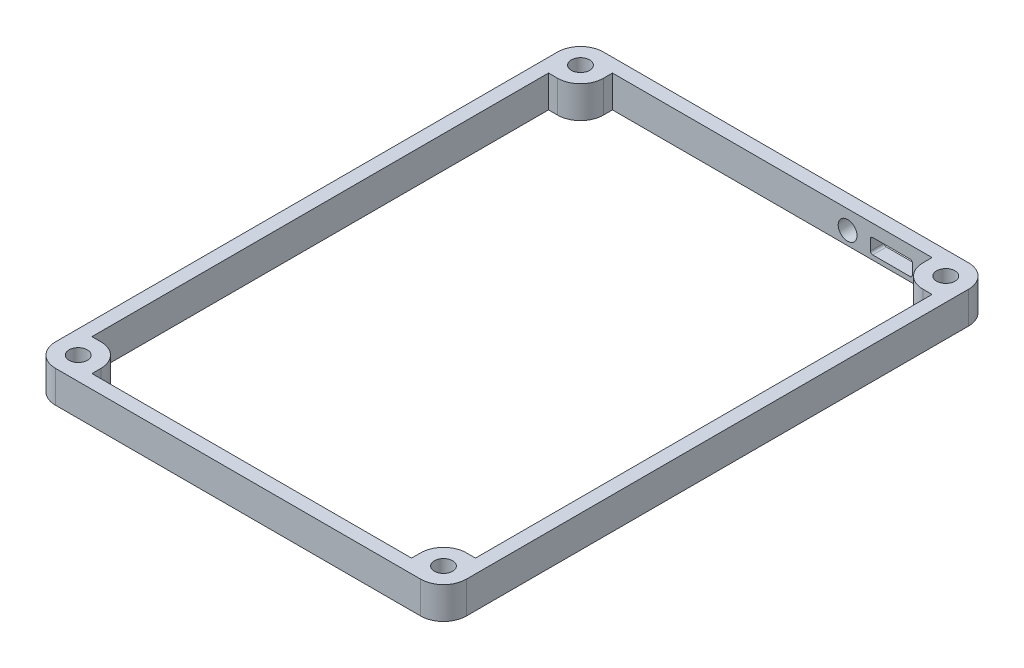
SolidWorks part; units mm, degrees
ref_plane "前视基准面" through (0, 0, 0) normal (0, 0, 1) x (1, 0, 0)
ref_plane "上视基准面" through (0, 0, 0) normal (0, 1, 0) x (1, 0, 0)
ref_plane "右视基准面" through (0, 0, 0) normal (1, 0, 0) x (0, 0, -1)
sketch "草图3" plane through (0, 0, 0) normal (0, 1, 0) x (-1, 0, 0)
  line L0 (-42, -50) -> (-42, 50)
  line L1 (-35, -57) -> (35, -57)
  line L3 (-45, 60) -> (45, 60)
  line L4 (42, -50) -> (42, 50)
  line L5 (0, 55) -> (0, -55) construction
  line L6 (-40, 0) -> (40, 0) construction
  line L7 (-45, 60) -> (-45, -60)
  line L8 (-45, -60) -> (45, -60)
  line L9 (-42, 50) -> (-35, 50)
  line L10 (-35, 57) -> (-35, 50)
  line L11 (45, 60) -> (45, -60)
  line L12 (0, -60) -> (0, 60) construction
  line L13 (42, 50) -> (35, 50)
  line L14 (35, 57) -> (35, 50)
  line L15 (-45, 0) -> (45, 0) construction
  line L17 (42, -50) -> (35, -50)
  line L18 (35, -57) -> (35, -50)
  line L21 (-42, -50) -> (-35, -50)
  line L22 (-35, -57) -> (-35, -50)
  line L23 (-35, 57) -> (35, 57)
  line L27 (0, 60) -> (0, -60) construction
  line L28 (-45, 0) -> (45, 0) construction
  line L33 (0, -60) -> (0, 60) construction
  line L34 (45, 0) -> (-45, 0) construction
  circle A0 centre (40, 55) radius 2
  circle A1 centre (40, -55) radius 2
  circle A2 centre (-40, -55) radius 2
  circle A3 centre (-40, 55) radius 2
  point P0 (0, 0)
  point P1 (0, 0)
  point P4 (0, 0)
  point P34 (0, 0)
  dimension "D11" = 7
  dimension "D15" = 5
  dimension "D1" = 120
  dimension "D2" = 90
  dimension "D3" = 7
  dimension "D4" = 7
  dimension "D5" = 3
  dimension "D6" = 7
  dimension "D7" = 7
  dimension "D8" = 3
  dimension "D9" = 7
  dimension "D10" = 7
  dimension "D12" = 7
  dimension "D13" = 3
  dimension "D14" = 7
  dimension "D16" = 5
extrude "凸台-拉伸2" add sketch "草图3" along normal blind 7 separate body
fillet "圆角1" radius 5 3 edges at (45, 3.5, 60) (-45, 3.5, 60) (45, 3.5, -60)
fillet "圆角2" radius 5 1 edges at (-45, 3.5, -60)
fillet "圆角3" radius 5 1 edges at (35, 3.5, -50)
fillet "圆角4" radius 5 1 edges at (-35, 3.5, -50)
fillet "圆角5" radius 5 1 edges at (35, 3.5, 50)
fillet "圆角6" radius 5 1 edges at (-35, 3.5, 50)
sketch "草图4" plane through (0, 0, -60) normal (0, 0, -1) x (-1, 0, 0)
  line L1 (-30.7, 4.3) -> (-21.5, 4.3)
  line L2 (-30.7, 4.3) -> (-30.7, 1)
  line L3 (-30.7, 1) -> (-21.5, 1)
  line L4 (-21.5, 4.3) -> (-21.5, 1)
  line L5 (-40, 0) -> (40, 0) construction
  line L6 (-40, 7) -> (-40, 0) construction
  dimension "D1" = 3.3
  dimension "D2" = 1
  dimension "D3" = 9.2
  dimension "D4" = 9.3
extrude "切除-拉伸1" cut sketch "草图4" against normal blind 3
fillet "圆角7" radius 0.5 1 edges at (21.5, 1, -58.5)
fillet "圆角8" radius 0.5 1 edges at (21.5, 4.3, -58.5)
fillet "圆角9" radius 0.5 1 edges at (30.7, 1, -58.5)
fillet "圆角10" radius 0.5 1 edges at (30.7, 4.3, -58.5)
sketch "草图5" plane through (0, 0, -60) normal (0, 0, -1) x (-1, 0, 0)
  line L0 (-40, 0) -> (40, 0) construction
  line L1 (-21.5, 1.5) -> (-21.5, 3.8) construction
  circle A0 centre (-16.5, 2.9133) radius 2.0585
  point P2 (0, 0)
  point P3 (-16.708, 2.9133)
  dimension "D1" = 2.9133
  dimension "D2" = 5
extrude "切除-拉伸2" cut sketch "草图5" against normal blind 3
